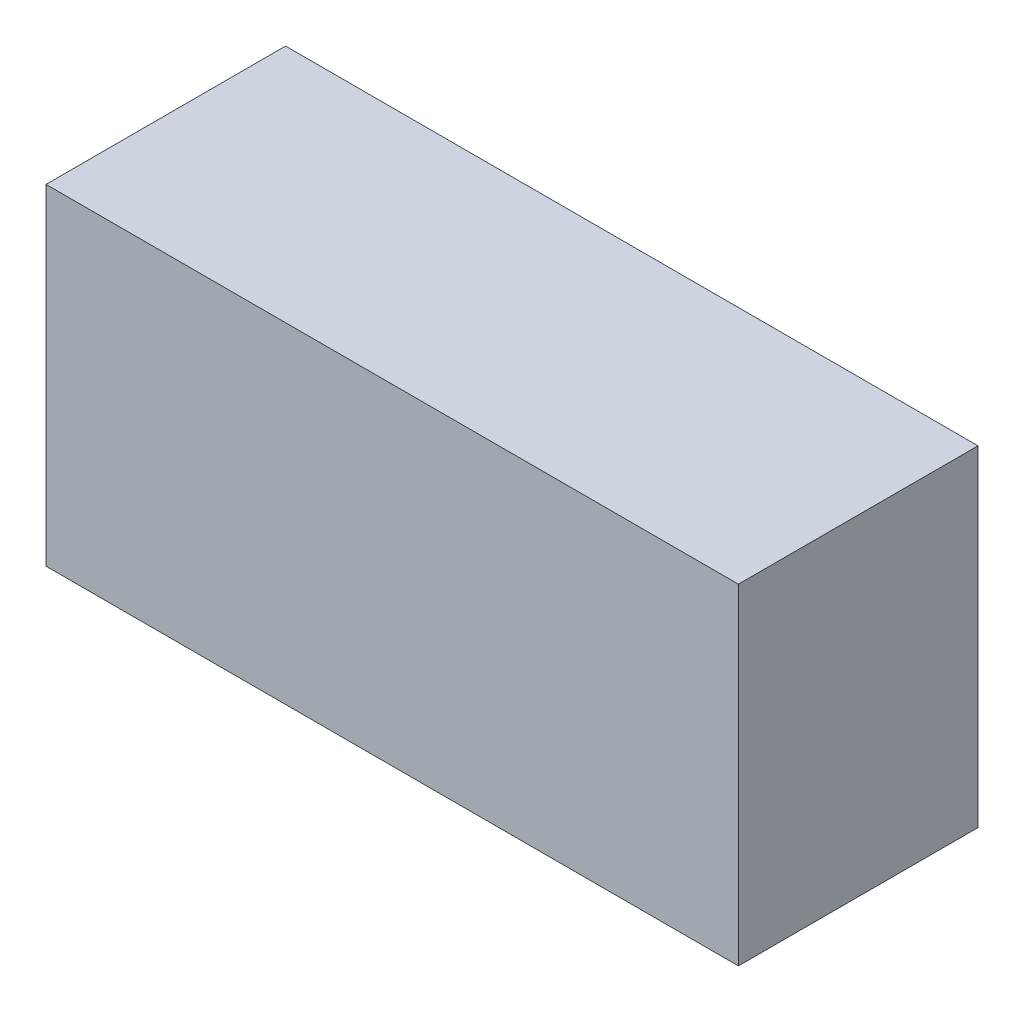
SolidWorks part; units mm, degrees
ref_plane "Front Plane" through (0, 0, 0) normal (0, 0, 1) x (1, 0, 0)
ref_plane "Top Plane" through (0, 0, 0) normal (0, 1, 0) x (1, 0, 0)
ref_plane "Right Plane" through (0, 0, 0) normal (1, 0, 0) x (0, 0, -1)
sketch "Sketch1" plane through (0, 0, 0) normal (0, 0, 1) x (1, 0, 0)
  line L0 (-14.45, -6.9) -> (14.45, -6.9)
  line L1 (14.45, -6.9) -> (14.45, 6.9)
  line L2 (14.45, 6.9) -> (-14.45, 6.9)
  line L3 (-14.45, 6.9) -> (-14.45, -6.9)
extrude "Boss-Extrude1" add sketch "Sketch1" along normal blind 10 from offset 0
